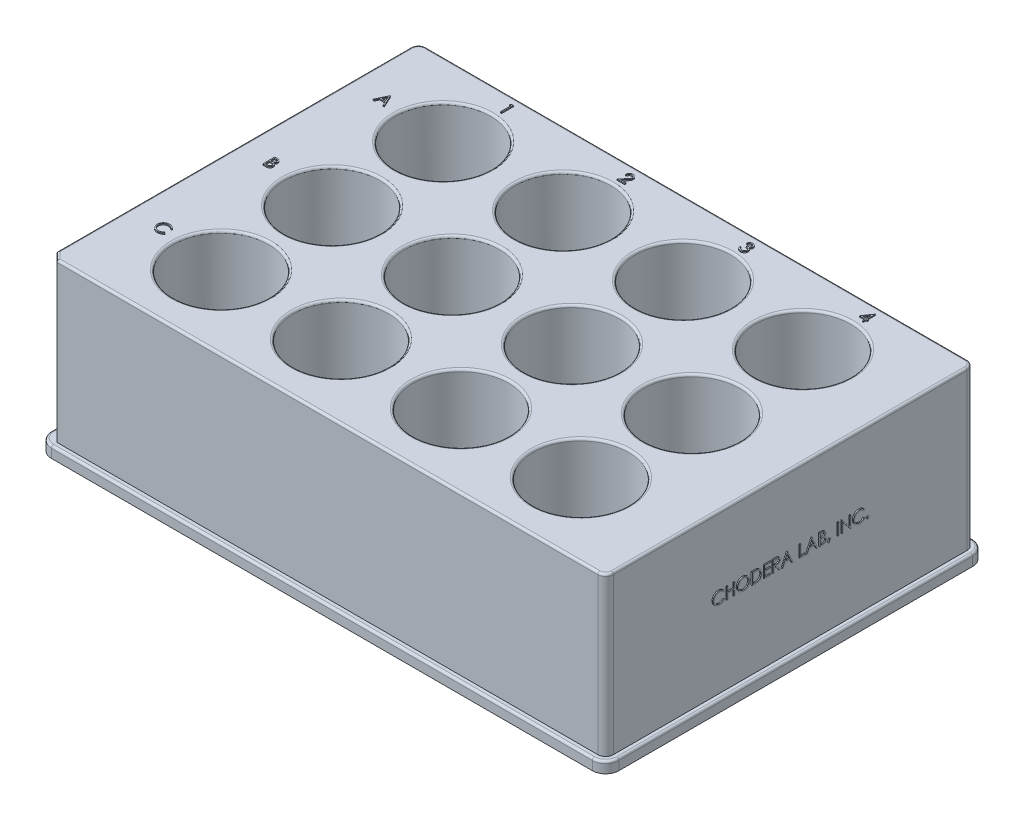
SolidWorks part; units mm, degrees
ref_plane "Front Plane" through (0, 0, 0) normal (0, 0, 1) x (1, 0, 0)
ref_plane "Top Plane" through (0, 0, 0) normal (0, 1, 0) x (1, 0, 0)
ref_plane "Right Plane" through (0, 0, 0) normal (1, 0, 0) x (0, 0, -1)
sketch "Sketch1" plane through (0, 0, 0) normal (0, 1, 0) x (1, 0, 0)
  line L0 (-63.875, -42.8) -> (63.875, 42.8) construction
  line L1 (-63.875, -42.8) -> (63.875, -42.8)
  line L2 (-63.875, -42.8) -> (-63.875, 42.8)
  line L3 (-63.875, 42.8) -> (63.875, 42.8)
  line L4 (63.875, -42.8) -> (63.875, 42.8)
  point P4 (0, 0)
  dimension "D1" = 85.6
  dimension "D2" = 127.75
extrude "Boss-Extrude1" add sketch "Sketch1" along normal blind 38.1
fillet "Fillet1" radius 3 4 edges at (-63.875, 19.05, -42.8) (-63.875, 19.05, 42.8) (63.875, 19.05, 42.8) (63.875, 19.05, -42.8)
sketch "Sketch3" plane through (0, 38.1, 0) normal (0, 1, 0) x (1, 0, 0)
  line L0 (-63.875, 39.8) -> (-63.875, -39.8) construction
  line L1 (60.875, 42.8) -> (-60.875, 42.8) construction
  line L2 (63.875, -39.8) -> (63.875, 39.8) construction
  line L3 (-60.875, -42.8) -> (60.875, -42.8) construction
  line L4 (-63.875, 39.8) -> (-63.875, -39.8)
  line L5 (60.875, 42.8) -> (-60.875, 42.8)
  line L6 (63.875, -39.8) -> (63.875, 39.8)
  line L7 (-60.875, -42.8) -> (60.875, -42.8)
  line L8 (-62.625, 39.8) -> (-62.625, -39.8)
  line L9 (-60.875, -41.55) -> (60.875, -41.55)
  line L10 (62.625, -39.8) -> (62.625, 39.8)
  line L11 (60.875, 41.55) -> (-60.875, 41.55)
  line L12 (-62.625, -39.8) -> (-60.875, -41.55)
  arc A0 (-60.875, 42.8) -> (-63.875, 39.8) centre (-60.875, 39.8) ccw construction
  arc A1 (63.875, 39.8) -> (60.875, 42.8) centre (60.875, 39.8) ccw construction
  arc A2 (60.875, -42.8) -> (63.875, -39.8) centre (60.875, -39.8) ccw construction
  arc A3 (-63.875, -39.8) -> (-60.875, -42.8) centre (-60.875, -39.8) ccw construction
  arc A4 (-60.875, 42.8) -> (-63.875, 39.8) centre (-60.875, 39.8) ccw
  arc A5 (63.875, 39.8) -> (60.875, 42.8) centre (60.875, 39.8) ccw
  arc A6 (60.875, -42.8) -> (63.875, -39.8) centre (60.875, -39.8) ccw
  arc A7 (-63.875, -39.8) -> (-60.875, -42.8) centre (-60.875, -39.8) ccw
  arc A9 (60.875, -41.55) -> (62.625, -39.8) centre (60.875, -39.8) ccw
  arc A10 (62.625, 39.8) -> (60.875, 41.55) centre (60.875, 39.8) ccw
  arc A11 (-60.875, 41.55) -> (-62.625, 39.8) centre (-60.875, 39.8) ccw
  arc A12 (-62.625, -39.8) -> (-60.875, -41.55) centre (-60.875, -39.8) ccw construction
  dimension "D1" = 1.25
extrude "Cut-Extrude2" cut sketch "Sketch3" against normal blind 35.6
sketch "Sketch5" plane through (0, 38.1, 0) normal (0, 1, 0) x (1, 0, 0)
  line L0 (0, 41.55) -> (0, -41.55) construction
  line L3 (60.875, 41.55) -> (-60.875, 41.55) construction
  line L6 (-60.875, -41.55) -> (60.875, -41.55) construction
  line L7 (-62.625, 0) -> (62.625, 0) construction
  line L8 (-62.625, 39.8) -> (-62.625, -39.8) construction
  line L9 (62.625, -39.8) -> (62.625, 39.8) construction
  line L11 (-13.5, 0) -> (0, 0) construction
  line L12 (-40.5, 25) -> (-40.5, 0) construction
  circle A0 centre (-40.5, 25) radius 10.75
  circle A1 centre (-13.5, 25) radius 10.75
  circle A2 centre (-13.5, 0) radius 10.75
  circle A3 centre (-13.5, -25) radius 10.75
  circle A4 centre (-40.5, 0) radius 10.75
  circle A5 centre (-40.5, -25) radius 10.75
  circle A6 centre (40.5, -25) radius 10.75
  circle A7 centre (40.5, 0) radius 10.75
  circle A8 centre (13.5, -25) radius 10.75
  circle A9 centre (13.5, 0) radius 10.75
  circle A10 centre (13.5, 25) radius 10.75
  circle A11 centre (40.5, 25) radius 10.75
  dimension "D1" = 21.5
  dimension "D2" = 27
  dimension "D3" = 27
  dimension "D4" = 25
extrude "Cut-Extrude3" cut sketch "Sketch5" against normal blind 35.6
fillet "Fillet3" radius 0.5 32 edges at (0, 38.1, -41.55) (62.1124, 38.1, -41.0374) (62.625, 38.1, 0) (62.1124, 38.1, 41.0374) (0, 38.1, 41.55) (-61.75, 38.1, 40.675) (-62.625, 38.1, 0) (-62.1124, 38.1, -41.0374) (-40.5, 38.1, -14.25) (40.5, 38.1, 14.25) (-13.5, 38.1, -14.25) (-13.5, 38.1, 10.75) (-13.5, 38.1, 35.75) (-40.5, 38.1, 10.75) (-40.5, 38.1, 35.75) (40.5, 38.1, -10.75) (13.5, 38.1, 14.25) (13.5, 38.1, -10.75) (13.5, 38.1, -35.75) (40.5, 38.1, -35.75) (-40.5, 2.5, 10.75) (-40.5, 2.5, 35.75) (-13.5, 2.5, 35.75) (13.5, 2.5, 14.25) (40.5, 2.5, 14.25) (40.5, 2.5, -10.75) (13.5, 2.5, -10.75) (-13.5, 2.5, 10.75) (-40.5, 2.5, -14.25) (-13.5, 2.5, -14.25) (13.5, 2.5, -35.75) (40.5, 2.5, -35.75)
fillet "Fillet5" radius 0.5 8 edges at (-62.9963, 2.5, 41.9213) (-63.875, 2.5, 0) (-62.9963, 2.5, -41.9213) (0, 2.5, -42.8) (62.9963, 2.5, -41.9213) (63.875, 2.5, 0) (62.9963, 2.5, 41.9213) (0, 2.5, 42.8)
sketch "Sketch6" plane through (0, 38.1, 0) normal (0, 1, 0) x (1, 0, 0)
  line L0 (0, 41.05) -> (0.1036, -41.05) construction
  line L1 (60.875, 41.05) -> (-60.875, 41.05) construction
  line L2 (-60.6679, -41.05) -> (60.875, -41.05) construction
  line L3 (-62.125, 0.1036) -> (62.125, 0) construction
  line L4 (-62.125, 39.8) -> (-62.125, -39.5929) construction
  line L5 (62.125, -39.8) -> (62.125, 39.8) construction
  line L6 (-62.125, 25.1036) -> (62.125, 25.1036) construction
  line L7 (-62.125, -24.8964) -> (62.125, -24.8964) construction
  line L8 (-40.5, 25) -> (-56.5, 25.1036) construction
  line L9 (-40.5, 0.0855) -> (-56.5, 0.0989) construction
  line L10 (-40.5, -25) -> (-56.5, -24.8964) construction
  line L11 (-40.5, 25) -> (-40.5, 37) construction
  line L12 (-40.5, 37) -> (-34.1408, 37) construction
  line L13 (-13.5, 37) -> (-8.9014, 37) construction
  line L14 (13.5, 37) -> (19.1549, 37) construction
  line L15 (40.5, 37) -> (49.1268, 37) construction
  line L16 (-13.5, 37) -> (-13.5, 25) construction
  line L17 (13.5, 37) -> (13.5, 25) construction
  line L18 (40.5, 37) -> (40.5, 25) construction
  text T0 "A" font "Century Gothic" height in points 10
  text T1 "B" font "Century Gothic" height in points 10
  text T2 "C" font "Century Gothic" height in points 10
  text T3 "1" font "Century Gothic" height in points 10
  text T4 "2" font "Century Gothic" height in points 10
  text T5 "3" font "Century Gothic" height in points 10
  text T6 "4" font "Century Gothic" height in points 10
  dimension "D1" = 25
  dimension "D2" = 25
  dimension "D3" = 16
  dimension "D4" = 12
shell "Shell1" thickness 1
extrude "Boss-Extrude2" add sketch "Sketch6" along normal blind 0.25
ref_plane "Plane1" through (13.5, 0, 0) normal (1, 0, 0) x (0, 0, -1)
ref_plane "Plane2" through (40.5, 0, 0) normal (1, 0, 0) x (0, 0, -1)
ref_plane "Plane3" through (-13.5, 0, 0) normal (1, 0, 0) x (0, 0, -1)
ref_plane "Plane4" through (-40.5, 0, 0) normal (1, 0, 0) x (0, 0, -1)
sketch "Sketch8" plane through (0, 37.1, 0) normal (0, -1, 0) x (1, 0, 0)
  line L0 (-40.5, 25) -> (29.75, 25) construction
  line L1 (61.625, 39.8) -> (61.625, -39.8) construction
  line L2 (-29.75, 0) -> (-24.25, 0) construction
  line L3 (-29.75, -25) -> (-24.25, -25) construction
  line L4 (-40.5, 25) -> (-40.5, 10.75) construction
  line L5 (60.875, -40.55) -> (-60.875, -40.55) construction
  line L6 (-13.5, 25) -> (-13.5, 10.75) construction
  line L7 (13.5, 25) -> (13.5, 10.75) construction
  line L8 (40.5, 14.25) -> (40.5, 10.75) construction
  line L9 (-61.625, 25) -> (-51.25, 25)
  line L10 (-61.625, -39.8) -> (-61.625, 39.3858) construction
  line L11 (-61.625, 0) -> (-51.25, 0)
  line L12 (-61.625, -25) -> (-51.25, -25)
  line L13 (-40.5, 40.55) -> (-40.5, 35.75)
  line L14 (-60.4608, 40.55) -> (60.875, 40.55) construction
  line L15 (-13.5, 40.55) -> (-13.5, 35.75)
  line L16 (13.5, 40.55) -> (13.5, 35.75)
  line L17 (40.5, 40.55) -> (40.5, 35.75)
  line L18 (-29.75, 25) -> (-24.25, 25)
  line L19 (-40.5, 14.25) -> (-40.5, 10.75)
  line L20 (-2.75, 25) -> (2.75, 25)
  line L21 (-13.5, 14.25) -> (-13.5, 10.75)
  line L22 (24.25, 25) -> (29.75, 25)
  line L23 (13.5, 14.25) -> (13.5, 10.75)
  line L24 (40.5, 14.25) -> (40.5, 10.75)
  line L25 (51.25, 25) -> (61.625, 25)
  line L26 (51.25, 25) -> (61.625, 25) construction
  line L27 (-40.5, -10.75) -> (-40.5, -14.25) construction
  line L28 (-40.5, -10.75) -> (-40.5, -14.25)
  line L29 (-29.75, 0) -> (-24.25, 0)
  line L30 (-13.5, -10.75) -> (-13.5, -14.25) construction
  line L31 (-13.5, -10.75) -> (-13.5, -14.25)
  line L32 (-2.75, 0) -> (2.75, 0) construction
  line L33 (-2.75, 0) -> (2.75, 0)
  line L34 (13.5, -10.75) -> (13.5, -14.25) construction
  line L35 (13.5, -10.75) -> (13.5, -14.25)
  line L36 (24.25, 0) -> (29.75, 0) construction
  line L37 (24.25, 0) -> (29.75, 0)
  line L38 (40.5, -10.75) -> (40.5, -14.25) construction
  line L39 (40.5, -10.75) -> (40.5, -14.25)
  line L40 (51.25, 0) -> (61.625, 0) construction
  line L41 (51.25, 0) -> (61.625, 0)
  line L42 (-40.5, -35.75) -> (-40.5, -40.55) construction
  line L43 (-40.5, -35.75) -> (-40.5, -40.55)
  line L44 (-29.75, -25) -> (-24.25, -25)
  line L45 (-13.5, -35.75) -> (-13.5, -40.55) construction
  line L46 (-13.5, -35.75) -> (-13.5, -40.55)
  line L47 (-2.75, -25) -> (2.75, -25) construction
  line L48 (-2.75, -25) -> (2.75, -25)
  line L49 (13.5, -35.75) -> (13.5, -40.55) construction
  line L50 (13.5, -35.75) -> (13.5, -40.55)
  line L51 (24.25, -25) -> (29.75, -25) construction
  line L52 (24.25, -25) -> (29.75, -25)
  line L53 (40.5, -35.75) -> (40.5, -40.55) construction
  line L54 (40.5, -35.75) -> (40.5, -40.55)
  line L55 (51.25, -25) -> (61.625, -25) construction
  line L56 (51.25, -25) -> (61.625, -25)
  circle A3 centre (-40.5, 25) radius 10.75 construction
  circle A4 centre (-13.5, 25) radius 10.75 construction
  circle A5 centre (13.5, 25) radius 10.75 construction
  circle A6 centre (40.5, 25) radius 10.75 construction
  circle A7 centre (-40.5, 0) radius 10.75 construction
  circle A8 centre (-13.5, 0) radius 10.75 construction
  circle A9 centre (13.5, 0) radius 10.75 construction
  circle A33 centre (40.5, 0) radius 10.75 construction
  circle A34 centre (-40.5, -25) radius 10.75 construction
  circle A35 centre (-13.5, -25) radius 10.75 construction
  circle A36 centre (13.5, -25) radius 10.75 construction
  circle A37 centre (40.5, -25) radius 10.75 construction
  circle A38 centre (-40.5, 25) radius 10.75 construction
  circle A39 centre (-13.5, 25) radius 10.75 construction
  circle A40 centre (13.5, 25) radius 10.75 construction
  circle A41 centre (40.5, 25) radius 10.75 construction
  circle A42 centre (-40.5, 0) radius 10.75 construction
  circle A43 centre (-13.5, 0) radius 10.75 construction
  circle A44 centre (13.5, 0) radius 10.75 construction
  circle A45 centre (40.5, 0) radius 10.75 construction
  circle A46 centre (-40.5, -25) radius 10.75 construction
  circle A47 centre (-13.5, -25) radius 10.75 construction
  circle A48 centre (13.5, -25) radius 10.75 construction
  circle A49 centre (40.5, -25) radius 10.75 construction
extrude "Extrude-Thin2" add sketch "Sketch8" along normal blind 25.4 thin thin type mid plane wall 1
sketch "Sketch10" plane through (62.625, 0, 0) normal (1, 0, 0) x (0, 0, -1)
  line L0 (-39.8, 20.05) -> (39.8, 20.05) construction
  line L1 (-39.8, 2.5) -> (-39.8, 37.6) construction
  line L2 (39.8, 2.5) -> (39.8, 37.6) construction
  text T0 "CHODERA LAB, INC." font "Century Gothic" height in points 10
extrude "Boss-Extrude3" add sketch "Sketch10" along normal blind 0.25
